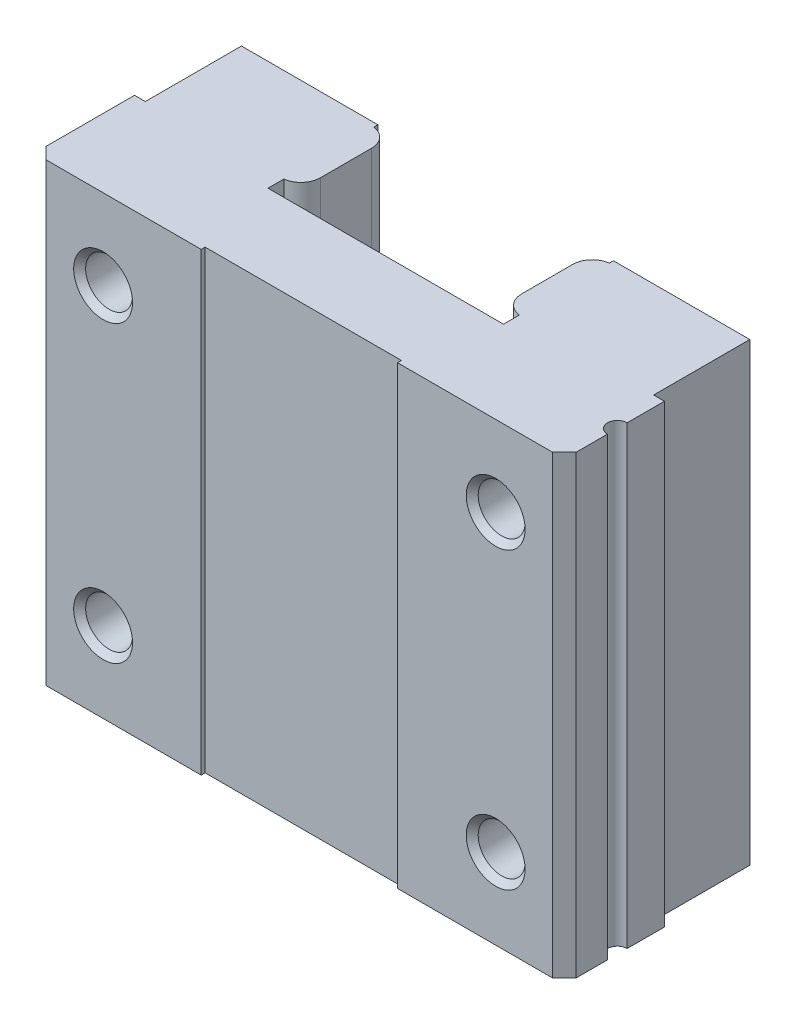
SolidWorks part; units mm, degrees
material "Aleación 1060"
ref_plane "Alzado" through (0, 0, 0) normal (0, 0, 1) x (1, 0, 0)
ref_plane "Planta" through (0, 0, 0) normal (0, 1, 0) x (1, 0, 0)
ref_plane "Vista lateral" through (0, 0, 0) normal (1, 0, 0) x (0, 0, -1)
ref_plane "Plano1" through (0, 0, 13) normal (0, 0, 1) x (1, 0, 0)
sketch "Croquis1" plane through (0, 0, 13) normal (0, 0, 1) x (1, 0, 0)
  line L0 (-13.5, 63.3005) -> (13.5, 63.3005)
  line L1 (13.5, 63.3005) -> (13.5, 86.4995)
  line L2 (13.5, 86.4995) -> (-13.5, 86.4995)
  line L3 (-13.5, 86.4995) -> (-13.5, 63.3005)
extrude "Saliente-Extruir1" add sketch "Croquis1" against normal blind 10
sketch "Croquis2" plane through (0, 63.3005, 0) normal (0, -1, 0) x (1, 0, 0)
  line L0 (-5.125, 3) -> (5.125, 3)
  line L1 (5.125, 3) -> (5.125, 6.8)
  line L2 (6, 7.7922) -> (6, 8.6)
  line L3 (6, 8.6) -> (-6, 8.6)
  line L4 (-6, 8.6) -> (-6, 7.7922)
  line L5 (-5.125, 6.8) -> (-5.125, 3)
  arc A0 (5.125, 6.8) -> (6, 7.7922) centre (6.125, 6.8) cw
  arc A1 (-6, 7.7922) -> (-5.125, 6.8) centre (-6.125, 6.8) cw
extrude "Cortar-Extruir1" cut sketch "Croquis2" against normal through all
sketch "Croquis3" plane through (0, 63.3005, 0) normal (0, -1, 0) x (1, 0, 0)
  line L0 (13.5, 7.9) -> (12.95, 7.9)
  line L1 (12.95, 7.9) -> (12.95, 3)
  line L2 (12.95, 3) -> (13.5, 3)
  line L3 (13.5, 3) -> (13.5, 7.9)
extrude "Cortar-Extruir2" cut sketch "Croquis3" against normal through all
sketch "Croquis4" plane through (0, 63.3005, 0) normal (0, -1, 0) x (1, 0, 0)
  line L0 (5.125, 4.2) -> (5.125, 3)
  line L1 (5.125, 3) -> (6, 3)
  line L2 (6, 3) -> (6, 3.2078)
  arc A0 (6, 3.2078) -> (5.125, 4.2) centre (6.125, 4.2) cw
extrude "Cortar-Extruir3" cut sketch "Croquis4" against normal through all
sketch "Croquis5" plane through (0, 63.3005, 0) normal (0, -1, 0) x (1, 0, 0)
  line L0 (-6, 3.2078) -> (-6, 3)
  line L1 (-6, 3) -> (-5.125, 3)
  line L2 (-5.125, 3) -> (-5.125, 4.2)
  arc A0 (-5.125, 4.2) -> (-6, 3.2078) centre (-6.125, 4.2) cw
extrude "Cortar-Extruir4" cut sketch "Croquis5" against normal blind 23.199
sketch "Croquis6" plane through (0, 63.3005, 0) normal (0, -1, 0) x (1, 0, 0)
  line L0 (-12.95, 7.9) -> (-13.5, 7.9)
  line L1 (-13.5, 7.9) -> (-13.5, 3)
  line L2 (-13.5, 3) -> (-12.95, 3)
  line L3 (-12.95, 3) -> (-12.95, 7.9)
extrude "Cortar-Extruir5" cut sketch "Croquis6" against normal through all
sketch "Croquis7" plane through (0, 63.3005, 0) normal (0, -1, 0) x (1, 0, 0)
  line L0 (5, 13) -> (-5, 13)
  line L1 (-5, 13) -> (-5, 12.8)
  line L2 (-5, 12.8) -> (5, 12.8)
  line L3 (5, 12.8) -> (5, 13)
extrude "Cortar-Extruir6" cut sketch "Croquis7" against normal through all
ref_plane "Plano2" through (0, 67.4, 0) normal (0, -1, 0) x (1, 0, 0)
sketch "Croquis8" plane through (0, 67.4, 0) normal (0, -1, 0) x (1, 0, 0)
  line L0 (-8.805, 13) -> (-10, 13)
  line L1 (-10, 13) -> (-10, 8.3072)
  line L2 (-10, 8.3072) -> (-8.8, 9)
  line L3 (-8.8, 9) -> (-8.8, 9.5)
  line L4 (-8.8, 9.5) -> (-8.805, 9.5)
  line L5 (-8.805, 9.5) -> (-8.805, 13)
  line L6 (-10, 13) -> (-10, 8.3071) construction
revolve "Cortar-Revolución1" cut sketch "Croquis8" angle 360 about L6
ref_plane "Plano3" through (0, 82.4, 0) normal (0, -1, 0) x (1, 0, 0)
sketch "Croquis9" plane through (0, 82.4, 0) normal (0, -1, 0) x (1, 0, 0)
  line L0 (-8.805, 13) -> (-10, 13)
  line L1 (-10, 13) -> (-10, 8.3072)
  line L2 (-10, 8.3072) -> (-8.8, 9)
  line L3 (-8.8, 9) -> (-8.8, 9.5)
  line L4 (-8.8, 9.5) -> (-8.805, 9.5)
  line L5 (-8.805, 9.5) -> (-8.805, 13)
  line L6 (-10, 13) -> (-10, 8.3071) construction
revolve "Cortar-Revolución2" cut sketch "Croquis9" angle 360 about L6
sketch "Croquis10" plane through (0, 67.4, 0) normal (0, -1, 0) x (1, 0, 0)
  line L0 (11.195, 13) -> (10, 13)
  line L1 (10, 13) -> (10, 8.3072)
  line L2 (10, 8.3072) -> (11.2, 9)
  line L3 (11.2, 9) -> (11.2, 9.5)
  line L4 (11.2, 9.5) -> (11.195, 9.5)
  line L5 (11.195, 9.5) -> (11.195, 13)
  line L6 (10, 13) -> (10, 8.3071) construction
revolve "Cortar-Revolución3" cut sketch "Croquis10" angle 360 about L6
sketch "Croquis11" plane through (0, 82.4, 0) normal (0, -1, 0) x (1, 0, 0)
  line L0 (11.195, 13) -> (10, 13)
  line L1 (10, 13) -> (10, 8.3072)
  line L2 (10, 8.3072) -> (11.2, 9)
  line L3 (11.2, 9) -> (11.2, 9.5)
  line L4 (11.2, 9.5) -> (11.195, 9.5)
  line L5 (11.195, 9.5) -> (11.195, 13)
  line L6 (10, 13) -> (10, 8.3071) construction
revolve "Cortar-Revolución4" cut sketch "Croquis11" angle 360 about L6
hole_wizard "Diámetro de taladro Ø1.0 (1)1" positions "Croquis13" profile "Croquis12" hole size "Ø1.0" standard "Ansi Metric"
sketch "Croquis13" plane through (0, 86.4995, 0) normal (0, 1, 0) x (-1, 0, 0)
  point P0 (-13.5, 10.3)
sketch "Croquis12" plane through (13.5, 86.4995, 10.3) normal (1, 0, 0) x (0, 0, 1)
  line L0 (0, 0) -> (0, 23.199)
  line L1 (0, 23.199) -> (0.5, 23.199)
  line L2 (0.5, 23.199) -> (0.5, 0)
  line L5 (0.5, 0) -> (0, 0)
  line L11 (0, -6.35) -> (0, 107.95) construction
  dimension "Diámetro de taladro hasta el siguiente" = 1
  dimension "Profundidad de taladro hasta el siguiente" = 23.199
chamfer "Chaflán1" distance 0.305 angle 45 4 edges at (8.805, 67.4, 13) (-11.195, 82.4, 13) (8.805, 82.4, 13) (-11.195, 67.4, 13)
chamfer "Chaflán2" distance 0.6 angle 45 2 edges at (13.5, 74.9, 13) (-13.5, 74.9, 13)
sketch "Croquis15" plane through (0, 0, 12.8) normal (0, 0, 1) x (1, 0, 0)
  line L0 (0, 86.4995) -> (0, 63.3005) construction
  line L1 (-5, 86.4995) -> (5, 86.4995) construction
  line L2 (-5, 63.3005) -> (5, 63.3005) construction
  line L3 (-50, 82.4) -> (50, 82.4) construction
  circle A0 centre (0, 82.4) radius 1.2
  dimension "D1" = 2.4
